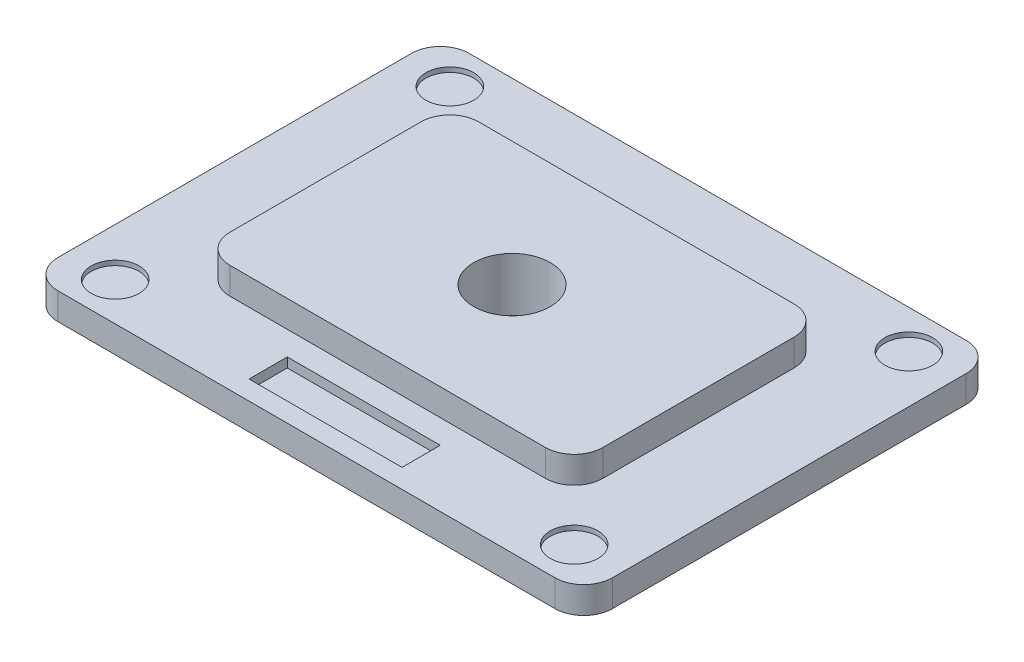
SolidWorks part; units mm, degrees
ref_plane "Front Plane" through (0, 0, 0) normal (0, 0, 1) x (1, 0, 0)
ref_plane "Top Plane" through (0, 0, 0) normal (0, 1, 0) x (1, 0, 0)
ref_plane "Right Plane" through (0, 0, 0) normal (1, 0, 0) x (0, 0, -1)
sketch "Sketch3" plane through (0, 0, 0) normal (0, 1, 0) x (1, 0, 0)
  line L0 (-36.83, 27.305) -> (36.83, 27.305)
  line L1 (36.83, 27.305) -> (36.83, -27.305)
  line L2 (36.83, -27.305) -> (-36.83, -27.305)
  line L3 (-36.83, -27.305) -> (-36.83, 27.305)
  line L4 (0, -55) -> (0, 55) construction
  line L5 (-55, 0) -> (55, 0) construction
  point P2 (0, -27.305)
  point P7 (-36.83, 0)
  dimension "D1" = 73.66
  dimension "D2" = 54.61
extrude "Extruded Lower Plate" add sketch "Sketch3" along normal blind 3.556
sketch "Sketch4" plane through (0, 3.556, 0) normal (0, 1, 0) x (1, 0, 0)
  line L0 (-24.765, 16.51) -> (-24.765, -16.51)
  line L1 (-24.765, -16.51) -> (24.765, -16.51)
  line L2 (24.765, -16.51) -> (24.765, 16.51)
  line L3 (24.765, 16.51) -> (-24.765, 16.51)
  line L4 (0, -55) -> (0, 55) construction
  line L5 (-55, 0) -> (55, 0) construction
  point P3 (0, -16.51)
  point P7 (-24.765, 0)
  dimension "D1" = 49.53
  dimension "D2" = 33.02
extrude "Extruded Upper Plate" add sketch "Sketch4" along normal blind 3.556
fillet "Plate Corner Fillet" radius 3.81 8 edges at (-24.765, 5.334, 16.51) (-24.765, 5.334, -16.51) (-36.83, 1.778, -27.305) (24.765, 5.334, -16.51) (36.83, 1.778, -27.305) (-36.83, 1.778, 27.305) (24.765, 5.334, 16.51) (36.83, 1.778, 27.305)
hole_wizard "0.4D Hole" positions "Sketch5" profile "Sketch6" hole size "1/16" standard "ANSI Inch" end condition through all
sketch "Sketch5" plane through (0, 7.112, 0) normal (0, 1, 0) x (1, 0, 0)
  point P0 (0, 0)
sketch "Sketch6" plane through (0, 7.112, 0) normal (1, 0, 0) x (0, 0, 1)
  line L0 (0, 0) -> (0, 7.112)
  line L1 (0, 7.112) -> (5.08, 7.112)
  line L2 (5.08, 7.112) -> (5.08, 0)
  line L5 (5.08, 0) -> (0, 0)
  line L11 (0, -6.35) -> (0, 107.95) construction
  dimension "Thru Hole Dia." = 10.16
  dimension "Thru Hole Depth" = 7.112
sketch "Sketch9" plane through (0, 3.556, 0) normal (0, 1, 0) x (1, 0, 0)
  line L0 (-33.02, -27.305) -> (33.02, -27.305) construction
  line L1 (-10.16, -19.685) -> (10.16, -19.685)
  line L2 (-10.16, -19.685) -> (-10.16, -24.765)
  line L3 (-10.16, -24.765) -> (10.16, -24.765)
  line L4 (10.16, -19.685) -> (10.16, -24.765)
  line L5 (0, -3.9116) -> (0, 3.9116) construction
  point P6 (0, -24.765)
  dimension "D1" = 20.32
  dimension "D2" = 5.08
  dimension "D3" = 2.54
extrude "Extruded Rectangular Cut" cut sketch "Sketch9" against normal blind 1.27
hole_wizard "4X 0.25D Pins" positions "Sketch10" profile "Sketch11" hole size "1/16" standard "ANSI Inch"
sketch "Sketch10" plane through (0, 3.556, 0) normal (0, 1, 0) x (1, 0, 0)
  line L0 (-33.02, -27.305) -> (33.02, -27.305) construction
  line L1 (-36.83, 23.495) -> (-36.83, -23.495) construction
  line L2 (36.83, -23.495) -> (36.83, 23.495) construction
  line L3 (33.02, 27.305) -> (-33.02, 27.305) construction
  point P0 (-30.48, -22.225)
  point P2 (-30.48, 22.225)
  point P4 (30.48, 22.225)
  point P6 (30.48, -22.225)
  dimension "D1" = 5.08
  dimension "D2" = 6.35
  dimension "D3" = 6.35
  dimension "D4" = 5.08
sketch "Sketch11" plane through (-30.48, 3.556, 22.225) normal (1, 0, 0) x (0, 0, 1)
  line L0 (0, 0) -> (0, 0.635)
  line L1 (0, 0.635) -> (3.175, 0.635)
  line L2 (3.175, 0.635) -> (3.175, 0)
  line L5 (3.175, 0) -> (0, 0)
  line L10 (0, 0.635) -> (-3.175, 0.635) construction
  line L11 (0, -6.35) -> (0, 107.95) construction
  dimension "Hole Dia." = 6.35
  dimension "Hole Depth" = 0.635
  dimension "Drill Angle" = 180
